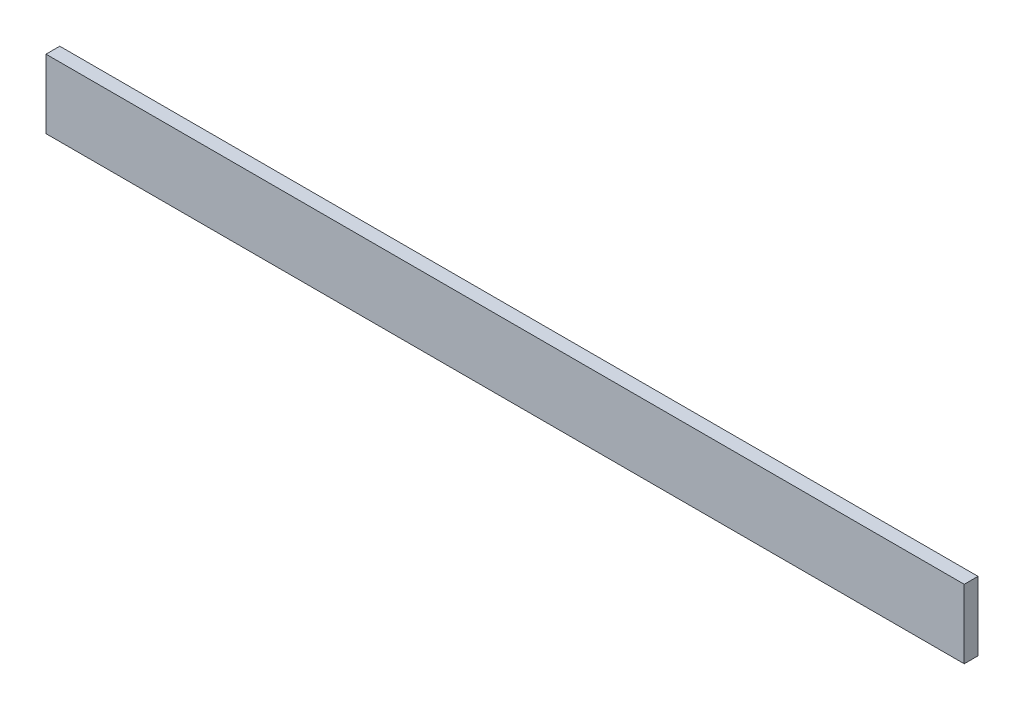
SolidWorks part; units mm, degrees
material "Pine"
ref_plane "Piano frontale" through (0, 0, 0) normal (0, 0, 1) x (1, 0, 0)
ref_plane "Piano superiore" through (0, 0, 0) normal (0, 1, 0) x (1, 0, 0)
ref_plane "Piano destro" through (0, 0, 0) normal (1, 0, 0) x (0, 0, -1)
sketch "Sketch1" plane through (0, 0, 0) normal (0, 0, 1) x (1, 0, 0)
  line L1 (0, 0) -> (100, 0)
  line L2 (0, 0) -> (0, 7.5)
  line L3 (0, 7.5) -> (100, 7.5)
  line L4 (100, 0) -> (100, 7.5)
  dimension "D1" = 7.5
  dimension "D2" = 100
extrude "Boss-Extrude1" add sketch "Sketch1" along normal blind 1.5
scale "Scale1" scale about origin uniform scaling yes scale factor 10
